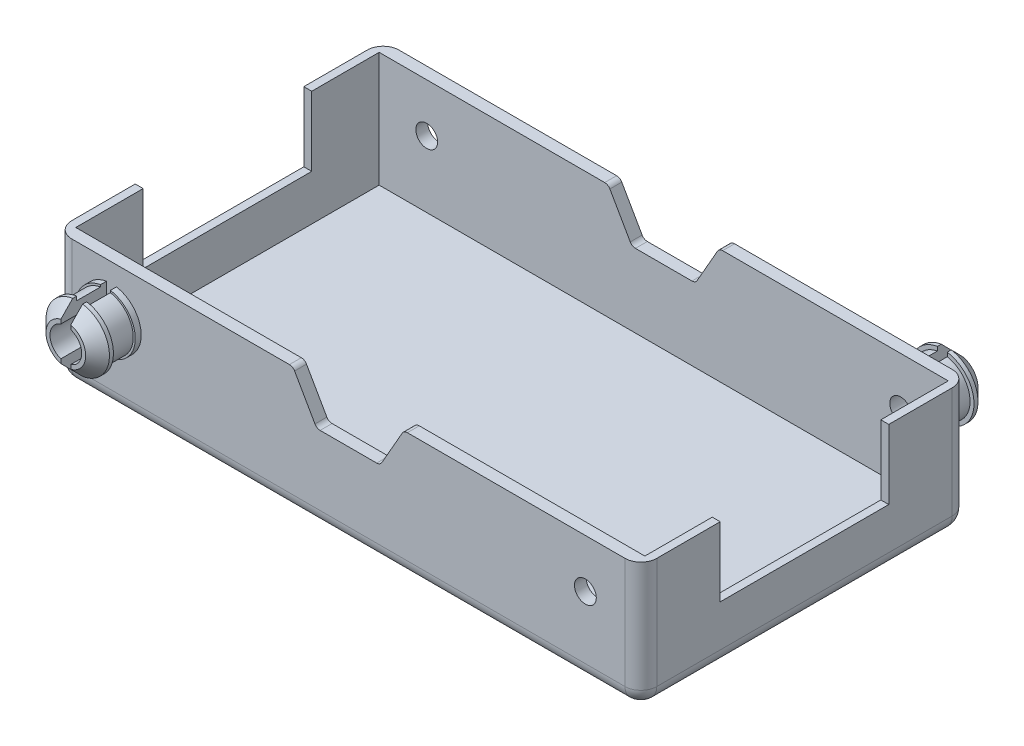
SolidWorks part; units mm, degrees
ref_plane "Front Plane" through (0, 0, 0) normal (0, 0, 1) x (1, 0, 0)
ref_plane "Top Plane" through (0, 0, 0) normal (0, 1, 0) x (1, 0, 0)
ref_plane "Right Plane" through (0, 0, 0) normal (1, 0, 0) x (0, 0, -1)
sketch "Sketch1" plane through (0, 0, 0) normal (0, 1, 0) x (1, 0, 0)
  line L1 (0, 0) -> (147.5, 0)
  line L2 (0, 0) -> (0, 82.5)
  line L3 (0, 82.5) -> (147.5, 82.5)
  line L4 (147.5, 0) -> (147.5, 82.5)
  dimension "D1" = 147.5
  dimension "D2" = 82.5
extrude "Boss-Extrude1" add sketch "Sketch1" along normal blind 32
shell "Shell1" thickness 3
fillet "Fillet1" radius 4 8 edges at (73.75, 0, 0) (147.5, 0, -41.25) (73.75, 0, -82.5) (0, 0, -41.25) (147.5, 16, -82.5) (147.5, 16, 0) (0, 16, -82.5) (0, 16, 0)
sketch "Sketch4" plane through (3, 0, 0) normal (1, 0, 0) x (0, 0, -1)
  line L4 (3, 3) -> (79.5, 3)
  line L5 (79.5, 3) -> (79.5, 32)
  line L6 (79.5, 32) -> (3, 32)
  line L7 (79.5, 3) -> (79.5, 32)
  line L8 (3, 3) -> (79.5, 3)
  line L10 (79.5, 32) -> (3, 32)
  line L12 (3, 32) -> (3, 3)
  line L13 (3, 32) -> (3, 3)
  dimension "D1" = 0
extrude "Cut-Extrude1" cut sketch "Sketch4" along normal offset from surface (143.5 mm away) 2 from offset 1
sketch "Sketch5" plane through (147.5, 0, 0) normal (1, 0, 0) x (0, 0, -1)
  line L0 (4, 32) -> (78.5, 32) construction
  line L1 (20, 32) -> (62.5, 32)
  line L2 (20, 32) -> (20, 14.5)
  line L3 (20, 14.5) -> (62.5, 14.5)
  line L4 (62.5, 32) -> (62.5, 14.5)
  line L6 (78.5, 0) -> (4, 0) construction
  line L7 (41.25, 4) -> (41.25, 46.3808) construction
  line L8 (4, 4) -> (78.5, 4) construction
  point P12 (41.25, 14.5)
  dimension "D1" = 42.5
  dimension "D2" = 14.5
extrude "Cut-Extrude2" cut sketch "Sketch5" against normal up to surface (147.5 mm away) up to face at (0, 18, -41.25)
sketch "Sketch6" plane through (0, 0, 0) normal (0, 0, 1) x (1, 0, 0)
  line L0 (4, 32) -> (143.5, 32) construction
  line L1 (65.75, 21.5) -> (81.75, 21.5)
  line L4 (81.75, 21.5) -> (81.75, 32) construction
  line L5 (65.75, 21.5) -> (73.75, 32) construction
  line L6 (73.75, 32) -> (81.75, 21.5) construction
  line L7 (81.75, 21.5) -> (87.75, 32)
  line L8 (65.75, 21.5) -> (59.75, 32)
  line L9 (59.75, 32) -> (87.75, 32)
  point P0 (73.75, 32)
  dimension "D1" = 8
  dimension "D2" = 14
  dimension "D3" = 14
  dimension "D4" = 10.5
extrude "Cut-Extrude3" cut sketch "Sketch6" against normal up to surface (82.5 mm away) up to face at (73.75, 18, -82.5)
fillet "Fillet2" radius 1.5 8 edges at (87.75, 32, -81) (81.75, 21.5, -81) (59.75, 32, -81) (65.75, 21.5, -81) (87.75, 32, -1.5) (81.75, 21.5, -1.5) (59.75, 32, -1.5) (65.75, 21.5, -1.5)
sketch "Sketch7" plane through (0, 0, 0) normal (0, 0, 1) x (1, 0, 0)
  line L1 (4, 4) -> (143.5, 4) construction
  line L2 (4, 32) -> (4, 4) construction
  line L3 (73.75, 4) -> (73.75, 37.0086) construction
  circle A0 centre (14, 19.75) radius 2.75
  circle A2 centre (133.5, 19.75) radius 2.75
  point P2 (14, 17)
  dimension "D1" = 5.5
  dimension "D2" = 13
  dimension "D4" = 10
extrude "Cut-Extrude4" cut sketch "Sketch7" against normal up to surface (82.5 mm away)
sketch "Sketch8" plane through (0, 0, 0) normal (0, 0, 1) x (1, 0, 0)
  line L0 (14, 19.75) -> (14, 30.7129) construction
  line L1 (12.75, 32) -> (12.75, 0) construction
  line L2 (4, 32) -> (58.8795, 32) construction
  line L3 (143.5, 0) -> (4, 0) construction
  line L4 (15.25, 32) -> (15.25, 0) construction
  circle A0 centre (14, 19.75) radius 8
  circle A2 centre (14, 19.75) radius 6
  circle A4 centre (14, 19.75) radius 5
  dimension "D1" = 16
  dimension "D2" = 3
  dimension "D3" = 1
  dimension "D4" = 1.25
  dimension "D5" = 2.5
sketch "Sketch9" plane through (0, 0, 0) normal (0, 0, 1) x (1, 0, 0)
  circle A0 centre (14, 19.75) radius 7.5
  circle A1 centre (14, 19.75) radius 2.75 construction
  circle A2 centre (14, 19.75) radius 2.75
  dimension "D1" = 15
extrude "Boss-Extrude3" add sketch "Sketch9" along normal blind 1.5
ref_axis "Axis1" through (14, 19.75, 0) along (0, 0, 1)
ref_plane "Plane1" through (14, 0, 0) normal (-1, 0, 0) x (0, 0, 1)
sketch "Sketch10" plane through (14, 0, 0) normal (-1, 0, 0) x (0, 0, 1)
  line L0 (0, 19.75) -> (33.8718, 19.75) construction
  line L1 (0, 32) -> (0, 0) construction
  line L2 (0, 19.75) -> (54.7881, 19.75) construction
  line L4 (11.5, 24.75) -> (8.5, 27.75)
  line L5 (8.5, 27.75) -> (7.5, 27.75)
  line L6 (7.5, 27.75) -> (7.5, 26.75)
  line L10 (1.5, 23.75) -> (11.5, 23.75)
  line L11 (11.5, 24.75) -> (11.5, 29.847) construction
  line L12 (8.5, 27.75) -> (15.1697, 21.0803) construction
  line L13 (11.5, 24.75) -> (11.5, 23.75)
  line L14 (7.5, 26.75) -> (1.5, 26.75)
  line L15 (1.5, 12.25) -> (1.5, 27.25) construction
  line L16 (1.5, 26.75) -> (1.5, 23.75)
  dimension "D1" = 1
  dimension "D2" = 1
  dimension "D3" = 4
  dimension "D4" = 135
  dimension "D5" = 1
  dimension "D6" = 8
  dimension "D7" = 10
revolve "Revolve1" add sketch "Sketch10" angle 360 about axis through (14, 19.75, 0) along (0, 0, 1)
sketch "Sketch11" plane through (0, 0, 0) normal (0, 0, 1) x (1, 0, 0)
  line L2 (12.75, 32) -> (12.75, 0) construction
  line L3 (12.75, 27.75) -> (15.25, 27.75)
  line L4 (15.25, 32) -> (15.25, 0) construction
  line L5 (15.25, 27.75) -> (15.25, 11.75)
  line L6 (15.25, 11.75) -> (12.75, 11.75)
  line L7 (12.75, 11.75) -> (12.75, 27.75)
extrude "Cut-Extrude5" cut sketch "Sketch11" along normal up to surface (11.5 mm away) up to face at (9, 19.75, 11.5)
ref_plane "Plane2" through (73.75, 0, 0) normal (-1, 0, 0) x (0, 0, 1)
ref_plane "Plane3" through (0, 0, -41.25) normal (0, 0, 1) x (1, 0, 0)
ref_plane "Plane4" through (57.5, 0, -57.5) normal (-0.7071, 0, 0.7071) x (0.7071, 0, 0.7071)
mirror "Mirror2" about plane through (73.75, 0, 0) normal (-1, 0, 0) of "Cut-Extrude5", "Revolve1", "Boss-Extrude3" second plane through (0, 0, -41.25) second plane normal (0, 0, 1)
sketch "Sketch12" plane through (0, 0, -82.5) normal (0, 0, -1) x (-1, 0, 0)
  line L0 (-4, 4) -> (-4, 32) construction
  line L1 (-29.2385, 30.4129) -> (-4, 30.4129)
  line L2 (-29.2385, 30.4129) -> (-29.2385, 7.9541)
  line L3 (-29.2385, 7.9541) -> (-4, 7.9541)
  line L4 (-4, 30.4129) -> (-4, 7.9541)
extrude "Cut-Extrude6" cut sketch "Sketch12" along normal up to surface (11.5 mm away) up to face at (11.125, 19.75, -94)
sketch "Sketch13" plane through (0, 0, 0) normal (0, 0, 1) x (1, 0, 0)
  line L0 (143.5, 4) -> (143.5, 32) construction
  line L1 (61.9909, 29.7891) -> (143.5, 29.7891)
  line L2 (61.9909, 29.7891) -> (61.9909, 10.4496)
  line L3 (61.9909, 10.4496) -> (143.5, 10.4496)
  line L4 (143.5, 29.7891) -> (143.5, 10.4496)
extrude "Cut-Extrude7" cut sketch "Sketch13" along normal up to surface (11.5 mm away)
